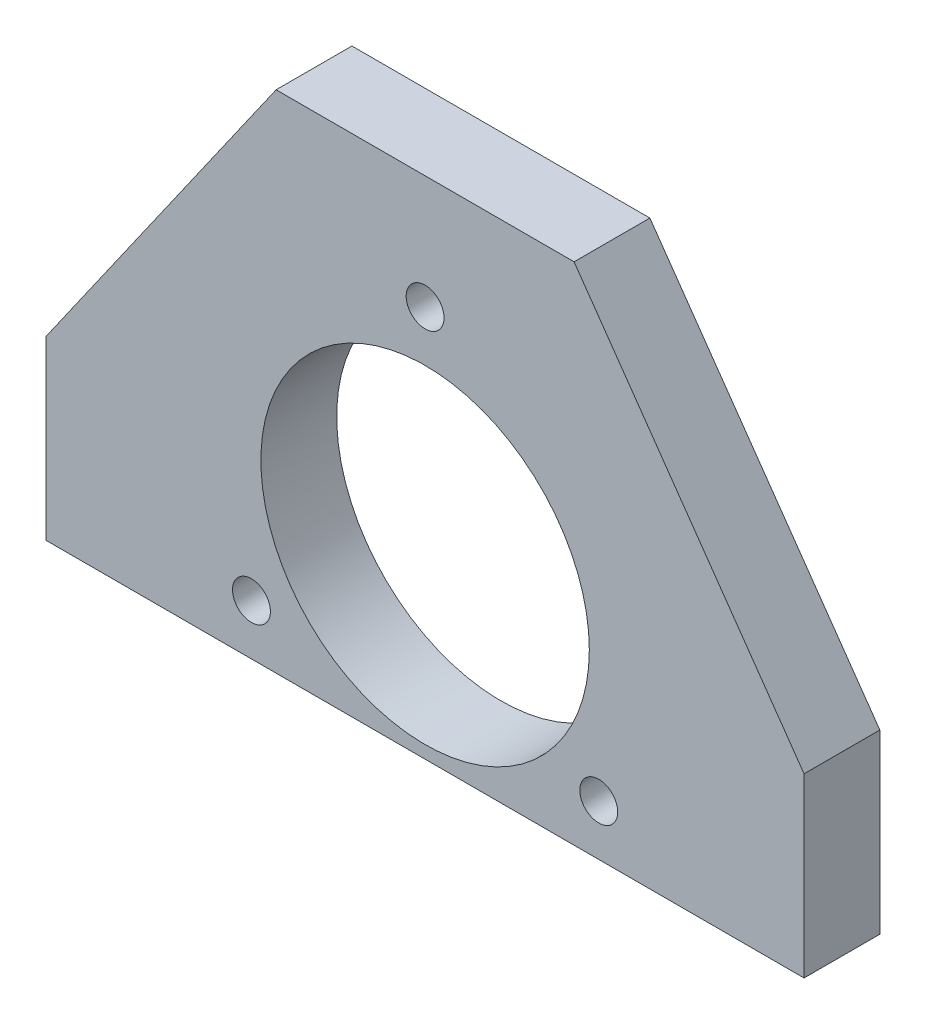
SolidWorks part; units mm, degrees
material "Balsa"
ref_plane "Plan de face" through (0, 0, 0) normal (0, 0, 1) x (1, 0, 0)
ref_plane "Plan de dessus" through (0, 0, 0) normal (0, 1, 0) x (1, 0, 0)
ref_plane "Plan de droite" through (0, 0, 0) normal (1, 0, 0) x (0, 0, -1)
sketch "Esquisse1" plane through (0, 0, 0) normal (0, 0, 1) x (1, 0, 0)
  line L0 (41.7946, 40) -> (60, 14)
  line L1 (0, 14) -> (0, 0)
  line L2 (60, 14) -> (60, 0)
  line L3 (18.2054, 40) -> (41.7946, 40)
  line L5 (18.2054, 40) -> (0, 14)
  line L6 (30, 40) -> (30, 0) construction
  line L15 (0, 0) -> (60, 0)
  circle A0 centre (30, 14) radius 13
  dimension "D1" = 26
  dimension "D2" = 14
  dimension "D14" = 125
  dimension "D15" = 125
extrude "Boss.-Extru.1" add sketch "Esquisse1" along normal blind 6
sketch "Esquisse2" plane through (0, 0, 6) normal (0, 0, 1) x (1, 0, 0)
  line L0 (16.2523, 4) -> (43.7477, 4) construction
  circle A0 centre (30, 14) radius 17 construction
  circle A1 centre (30, 14) radius 13 construction
  circle A2 centre (16.2523, 4) radius 1.5
  circle A3 centre (43.7477, 4) radius 1.5
  circle A4 centre (30, 31) radius 1.5
  dimension "D1" = 34
  dimension "D2" = 10
extrude "Enlèv. mat.-Extru.1" cut sketch "Esquisse2" against normal blind 10
